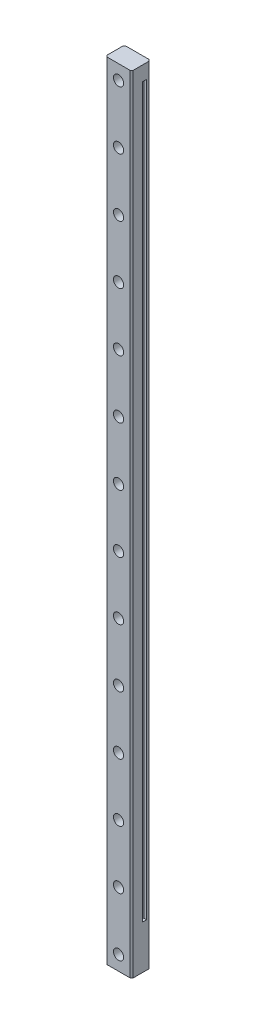
SolidWorks part; units mm, degrees
material "AISI 304"
ref_plane "前视基准面" through (0, 0, 0) normal (0, 0, 1) x (1, 0, 0)
ref_plane "上视基准面" through (0, 0, 0) normal (0, 1, 0) x (1, 0, 0)
ref_plane "右视基准面" through (0, 0, 0) normal (1, 0, 0) x (0, 0, -1)
sketch "草图1" plane through (0, 0, 0) normal (0, 1, 0) x (1, 0, 0)
  line L1 (-4.5, -3.25) -> (4.5, -3.25)
  line L2 (-4.5, -3.25) -> (-4.5, 3.25)
  line L3 (-4.5, 3.25) -> (4.5, 3.25)
  line L4 (4.5, -3.25) -> (4.5, 3.25)
  line L5 (-4.5, -3.25) -> (4.5, 3.25) construction
  line L6 (-4.5, 3.25) -> (4.5, -3.25) construction
  point P0 (0, 0)
  dimension "D1" = 9
  dimension "D2" = 6.5
extrude "凸台-拉伸1" add sketch "草图1" along normal blind 130 and the other way blind 140
sketch "草图2" plane through (0, 0, 0) normal (0, 1, 0) x (1, 0, 0)
  line L0 (0, 0) -> (4.5, 0) construction
  line L1 (4.5, -3.25) -> (4.5, 3.25) construction
  line L2 (0, 0) -> (0, 3.25) construction
  line L3 (4.5, 3.25) -> (-4.5, 3.25) construction
  line L4 (4.5, 1.89) -> (3.55, 1.89)
  line L5 (3.55, 1.89) -> (3.55, 0.41)
  line L6 (3.55, 0.41) -> (4.5, 0.41)
  line L7 (4.5, 1.89) -> (4.5, 0.41)
  line L8 (-3.55, 0.41) -> (-4.5, 0.41)
  line L9 (-3.55, 1.89) -> (-3.55, 0.41)
  line L10 (-4.5, 1.89) -> (-3.55, 1.89)
  line L11 (-4.5, 1.89) -> (-4.5, 0.41)
  dimension "D1" = 0.95
  dimension "D2" = 1.48
  dimension "D3" = 1.36
extrude "切除-拉伸1" cut sketch "草图2" against normal blind 125 and the other way blind 125
chamfer "倒角2" distance 0.5 angle 45 4 edges at (-4.5, -5, 3.25) (4.5, -5, 3.25) (4.5, -5, -3.25) (-4.5, -5, -3.25)
sketch "草图3" plane through (0, 0, -3.25) normal (0, 0, -1) x (-1, 0, 0)
  line L0 (0, 0) -> (0, -137.3682) construction
  line L1 (-4, -140) -> (4, -140) construction
  line L2 (4.5, 130) -> (4.5, -140) construction
  circle A0 centre (0, -135) radius 3
  circle A1 centre (0, -115) radius 3
  circle A2 centre (0, -95) radius 3
  circle A3 centre (0, -75) radius 3
  circle A4 centre (0, -55) radius 3
  circle A5 centre (0, -35) radius 3
  circle A6 centre (0, -15) radius 3
  circle A7 centre (0, 5) radius 3
  circle A8 centre (0, 25) radius 3
  circle A9 centre (0, 45) radius 3
  circle A10 centre (0, 65) radius 3
  circle A11 centre (0, 85) radius 3
  circle A12 centre (0, 105) radius 3
  circle A13 centre (0, 125) radius 3
  dimension "D1" = 6
  dimension "D5" = 6
  dimension "D8" = 6
  dimension "D9" = 20
  dimension "D2" = 5
  dimension "D4" = 20
  dimension "D6" = 20
  dimension "D7" = 4.5
  dimension "D10" = 4.5
  dimension "D3" = 12
extrude "切除-拉伸2" cut sketch "草图3" against normal blind 3.5
sketch "草图4" plane through (0, 0, 0.25) normal (0, 0, -1) x (-1, 0, 0)
  line L0 (0, 0) -> (0, 21.8734) construction
  circle A0 centre (0, -135) radius 1.75
  circle A1 centre (0, -115) radius 1.75
  circle A2 centre (0, -95) radius 1.75
  circle A3 centre (0, -75) radius 1.75
  circle A4 centre (0, -55) radius 1.75
  circle A5 centre (0, -35) radius 1.75
  circle A6 centre (0, -15) radius 1.75
  circle A7 centre (0, 5) radius 1.75
  circle A8 centre (0, 25) radius 1.75
  circle A9 centre (0, 45) radius 1.75
  circle A10 centre (0, 65) radius 1.75
  circle A11 centre (0, 85) radius 1.75
  circle A12 centre (0, 105) radius 1.75
  circle A13 centre (0, 125) radius 1.75
  circle A14 centre (0, 145) radius 1.75
  dimension "D1" = 3.5
  dimension "D3" = 20
  dimension "D2" = 15
extrude "切除-拉伸3" cut sketch "草图4" against normal blind 5
